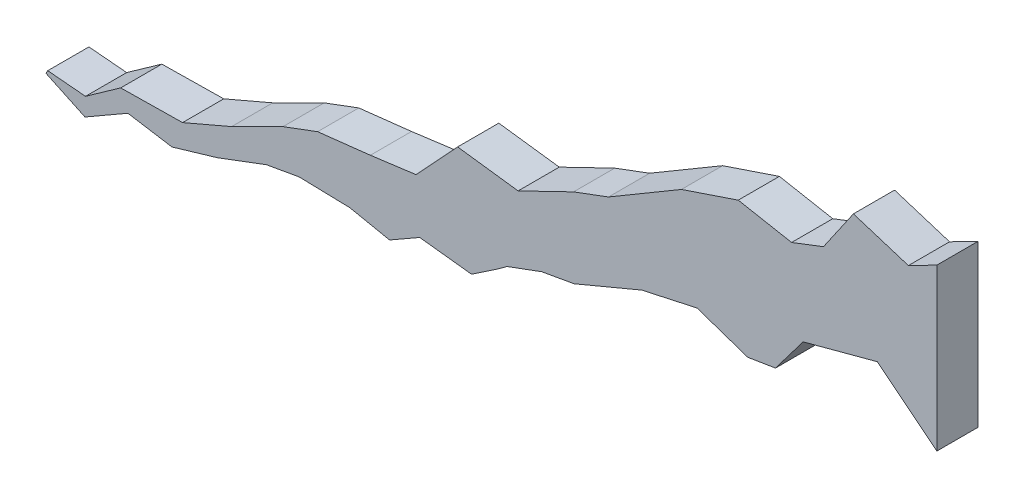
SolidWorks part; units mm, degrees
ref_plane "Ebene vorne" through (0, 0, 0) normal (0, 0, 1) x (1, 0, 0)
ref_plane "Ebene oben" through (0, 0, 0) normal (0, 1, 0) x (1, 0, 0)
ref_plane "Ebene rechts" through (0, 0, 0) normal (1, 0, 0) x (0, 0, -1)
sketch "Model" plane through (0, 0, 0) normal (0, 0, 1) x (1, 0, 0)
  line L42 (65.0641, 21.8076) -> (62.991, 20.7426)
  line L43 (62.991, 20.7426) -> (58.9841, 22.0027)
  line L44 (58.9841, 22.0027) -> (56.803, 18.8388)
  line L45 (56.803, 18.8388) -> (54.4795, 17.9444)
  line L46 (54.4795, 17.9444) -> (50.59, 18.6713)
  line L47 (50.59, 18.6713) -> (46.4536, 17.279)
  line L48 (46.4536, 17.279) -> (41.1341, 14.1429)
  line L49 (41.1341, 14.1429) -> (38.5897, 13.1928)
  line L50 (38.5897, 13.1928) -> (34.5476, 11.2338)
  line L51 (34.5476, 11.2338) -> (30.1385, 11.806)
  line L52 (30.1385, 11.806) -> (27.108, 8.5409)
  line L53 (27.108, 8.5409) -> (23.78, 8.1001)
  line L54 (23.78, 8.1001) -> (19.9361, 7.6648)
  line L55 (19.9361, 7.6648) -> (17.412, 6.7217)
  line L56 (17.412, 6.7217) -> (13.6665, 4.8514)
  line L57 (13.6665, 4.8514) -> (10.0942, 3.3184)
  line L58 (10.0942, 3.3184) -> (5.5816, 3.2524)
  line L59 (5.5816, 3.2524) -> (3.0187, 1.4378)
  line L60 (3.0187, 1.4378) -> (0.2676, 1.6817)
  line L61 (0.2676, 1.6817) -> (0.1393, 1.45)
  line L62 (0.1393, 1.45) -> (2.9813, 0.1127)
  line L63 (2.9813, 0.1127) -> (6.1038, 1.9118)
  line L64 (6.1038, 1.9118) -> (9.3163, 1.3905)
  line L65 (9.3163, 1.3905) -> (12.655, 2.3753)
  line L66 (12.655, 2.3753) -> (16.2205, 3.7167)
  line L67 (16.2205, 3.7167) -> (18.5922, 4.1362)
  line L68 (18.5922, 4.1362) -> (22.2788, 4.0404)
  line L69 (22.2788, 4.0404) -> (25.1785, 3.4514)
  line L70 (25.1785, 3.4514) -> (27.3781, 4.7079)
  line L71 (27.3781, 4.7079) -> (31.1542, 4.2752)
  line L72 (31.1542, 4.2752) -> (33.1201, 5.6028)
  line L73 (33.1201, 5.6028) -> (33.7439, 6.0592)
  line L74 (33.7439, 6.0592) -> (36.2735, 6.9932)
  line L75 (36.2735, 6.9932) -> (38.6239, 7.4095)
  line L76 (38.6239, 7.4095) -> (43.5681, 9.4807)
  line L77 (43.5681, 9.4807) -> (47.5879, 10.3601)
  line L78 (47.5879, 10.3601) -> (51.2897, 9.1002)
  line L79 (51.2897, 9.1002) -> (53.3064, 9.4304)
  line L80 (53.3064, 9.4304) -> (55.321, 12.0932)
  line L81 (55.321, 12.0932) -> (60.73, 13.5423)
  line L82 (60.73, 13.5423) -> (65.0641, 10.069)
  line L83 (65.0641, 10.069) -> (65.0641, 21.8076)
extrude "Aufsatz-Linear austragen1" add sketch "Model" along normal blind 3
